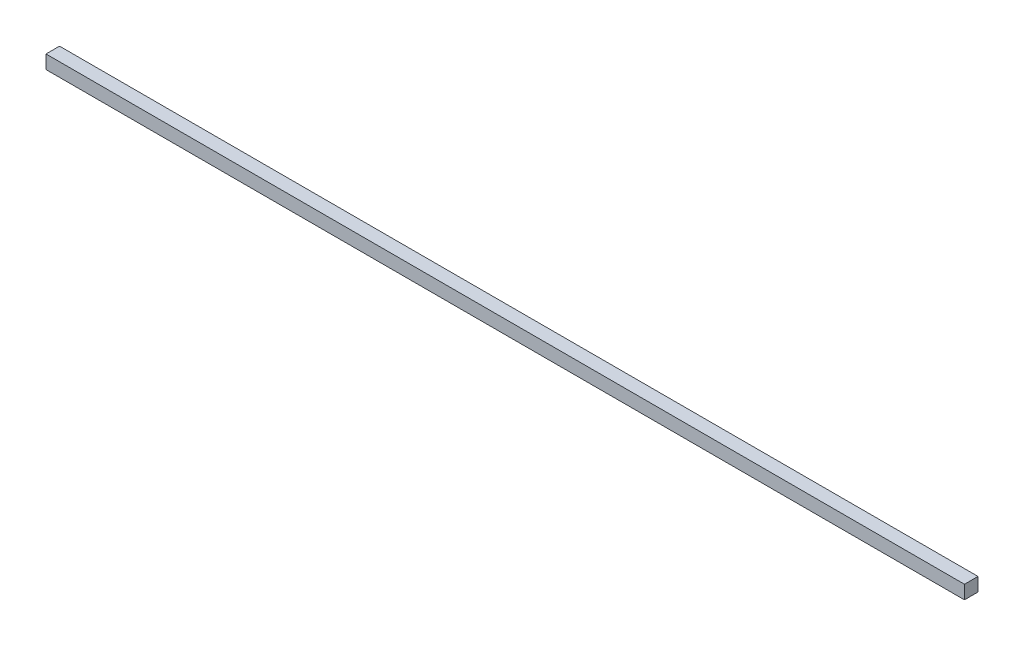
SolidWorks part; units mm, degrees
ref_plane "Front Plane" through (0, 0, 0) normal (0, 0, 1) x (1, 0, 0)
ref_plane "Top Plane" through (0, 0, 0) normal (0, 1, 0) x (1, 0, 0)
ref_plane "Right Plane" through (0, 0, 0) normal (1, 0, 0) x (0, 0, -1)
sketch "Sketch1" plane through (0, 0, 0) normal (0, 1, 0) x (1, 0, 0)
  line L1 (0, 0) -> (1357, 0)
  line L2 (0, 0) -> (0, 20)
  line L3 (0, 20) -> (1357, 20)
  line L4 (1357, 0) -> (1357, 20)
  dimension "D1" = 1357
  dimension "D2" = 20
extrude "Boss-Extrude1" add sketch "Sketch1" along normal blind 20
